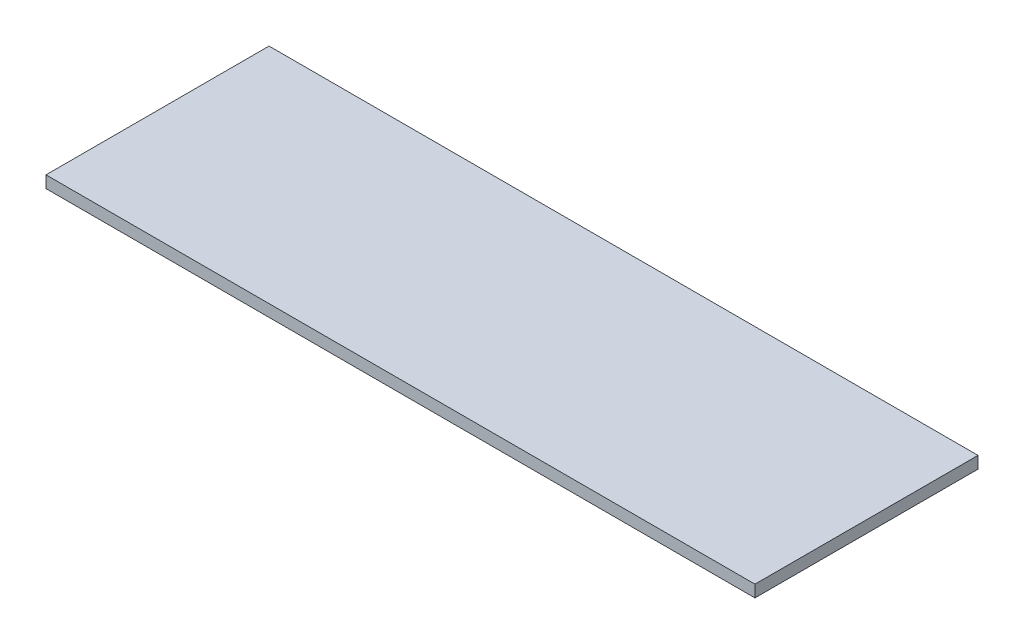
SolidWorks part; units mm, degrees
ref_plane "Front Plane" through (0, 0, 0) normal (0, 0, 1) x (1, 0, 0)
ref_plane "Top Plane" through (0, 0, 0) normal (0, 1, 0) x (1, 0, 0)
ref_plane "Right Plane" through (0, 0, 0) normal (1, 0, 0) x (0, 0, -1)
sketch "Sketch1" plane through (0, 0, 0) normal (0, 1, 0) x (1, 0, 0)
  line L1 (-89, 28) -> (89, 28)
  line L2 (-89, 28) -> (-89, -28)
  line L3 (-89, -28) -> (89, -28)
  line L4 (89, 28) -> (89, -28)
  line L5 (0, -28) -> (0, 28) construction
  line L6 (-89, 0) -> (89, 0) construction
  point P0 (0, 0)
  dimension "D1" = 178
  dimension "D2" = 56
extrude "Boss-Extrude1" add sketch "Sketch1" along normal blind 3
